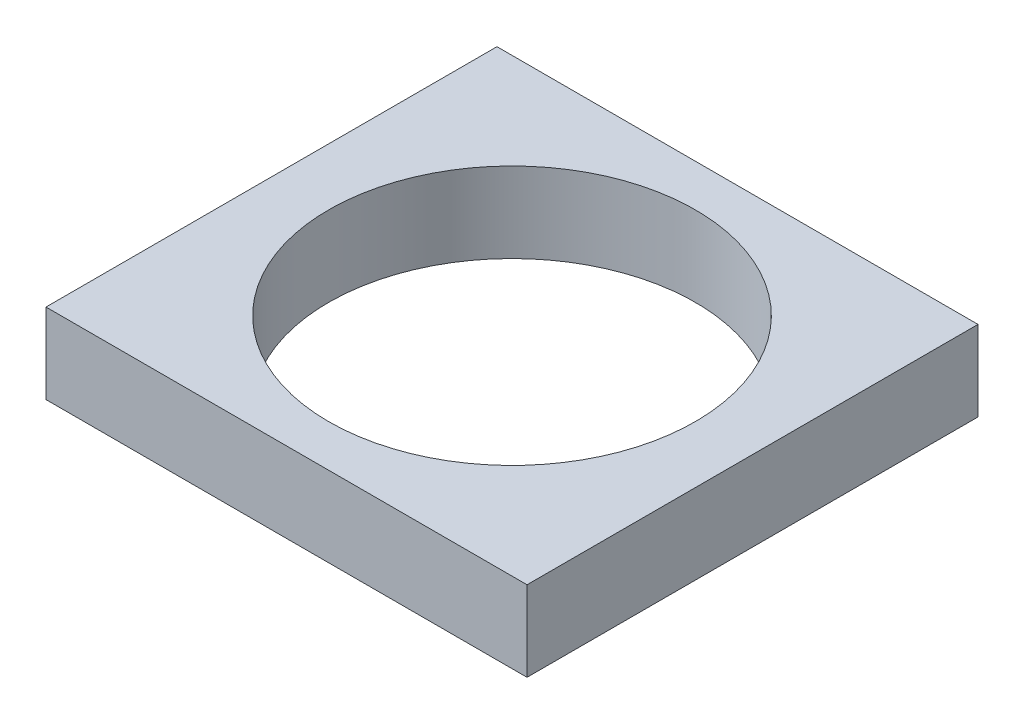
SolidWorks part; units mm, degrees
ref_plane "Front" through (0, 0, 0) normal (0, 0, 1) x (1, 0, 0)
ref_plane "Top" through (0, 0, 0) normal (0, 1, 0) x (1, 0, 0)
ref_plane "Right" through (0, 0, 0) normal (1, 0, 0) x (0, 0, -1)
sketch "Sketch1" plane through (0, 0, 0) normal (0, 1, 0) x (1, 0, 0)
  line L1 (0, 0) -> (24, 0)
  line L2 (0, 0) -> (0, -22.5)
  line L3 (0, -22.5) -> (24, -22.5)
  line L4 (24, 0) -> (24, -22.5)
  dimension "D1" = 24
  dimension "D2" = 22.5
extrude "Boss-Extrude1" add sketch "Sketch1" along normal blind 4
sketch "Sketch2" plane through (0, 4, 0) normal (0, 1, 0) x (1, 0, 0)
  line L0 (0, 0) -> (0, -22.5) construction
  line L1 (0, -22.5) -> (24, -22.5) construction
  circle A0 centre (12, -11.25) radius 9.15
  dimension "D1" = 18.3
  dimension "D2" = 12
  dimension "D3" = 11.25
extrude "Cut-Extrude1" cut sketch "Sketch2" against normal through all
